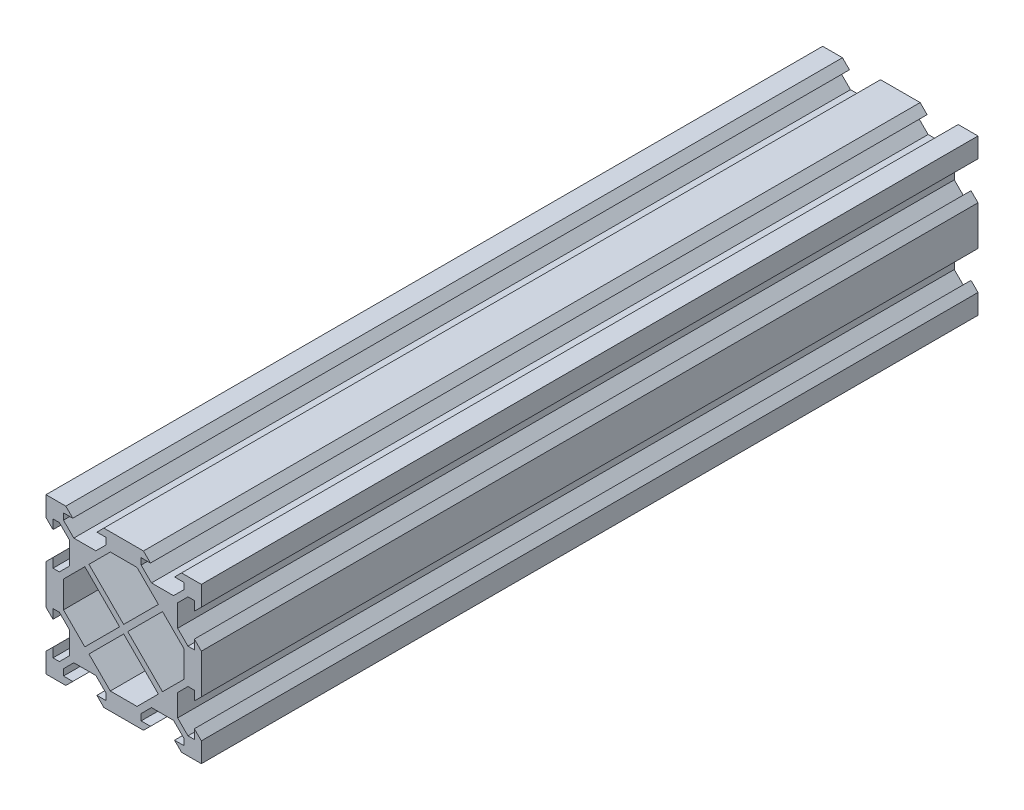
SolidWorks part; units mm, degrees
ref_plane "Front (XY)" through (0, 0, 0) normal (0, 0, 1) x (1, 0, 0)
ref_plane "Top (XZ)" through (0, 0, 0) normal (0, 1, 0) x (1, 0, 0)
ref_plane "Right (YZ)" through (0, 0, 0) normal (1, 0, 0) x (0, 0, -1)
sketch "Sketch2" plane through (0, 0, 0) normal (0, 0, 1) x (1, 0, 0)
  line L0 (-10, 10) -> (10, 10)
  line L1 (10, 10) -> (10, -10)
  line L2 (10, -10) -> (-10, -10)
  line L3 (-10, -10) -> (-10, 10)
  point P4 (0, -10)
  point P6 (10, 0)
  dimension "D1" = 20
  dimension "D2" = 20
extrude "Boss-Extrude1" add sketch "Sketch2" against normal blind 200
sketch "Sketch3" plane through (0, 0, 0) normal (0, 0, 1) x (1, 0, 0)
  line L0 (0, 0) -> (0, 10) construction
  line L1 (0, 10) -> (-3.1, 10) construction
  line L2 (10, 10) -> (-10, 10) construction
  line L3 (-3.1, 10) -> (-3.1, 8.2) construction
  line L4 (3.1, 10) -> (3.1, 8.2) construction
  line L5 (-3.1, 8.2) -> (-4.9, 10)
  line L6 (3.1, 8.2) -> (4.9, 10)
  line L7 (-3.1, 8.2) -> (-5.5, 8.2)
  line L8 (3.1, 8.2) -> (5.5, 8.2)
  line L9 (-5.5, 8.2) -> (-5.5, 6.56)
  line L10 (5.5, 8.2) -> (5.5, 6.56)
  line L11 (0, 10) -> (0, 3.9) construction
  line L12 (2.84, 3.9) -> (-2.84, 3.9)
  line L13 (-2.84, 3.9) -> (-5.5, 6.56)
  line L14 (2.84, 3.9) -> (5.5, 6.56)
  line L15 (-4.9, 10) -> (4.9, 10)
  point P21 (0, 3.9)
  dimension "D1" = 3.1
  dimension "D2" = 1.8
  dimension "D3" = 90
  dimension "D4" = 2.4
  dimension "D5" = 1.64
  dimension "D6" = 6.1
  dimension "D7" = 5.68
extrude "Cut-Extrude1" cut sketch "Sketch3" along normal through all and the other way through all
sketch "Sketch8" plane through (0, 0, 0) normal (1, 0, 0) x (0, 0, -1)
  line L0 (0, 0) -> (-11.2124, 0) construction
  line L1 (0, -10) -> (0, 10) construction
pattern_circular "CirPattern2" count 4 over 360 about axis through (0, 0, 0) along (0, 0, 1) of "Cut-Extrude1"
pattern_linear "LPattern1" count 2 spacing 20 along (0, 1, 0) count 2 spacing 20 along (1, 0, 0) of "Boss-Extrude1", "Cut-Extrude1", "CirPattern2"
sketch "Sketch9" plane through (0, 0, 0) normal (0, 0, 1) x (1, 0, 0)
  line L0 (14.5, 6.56) -> (17.16, 3.9) construction
  line L1 (16.1, 2.84) -> (13.44, 5.5) construction
  line L2 (2.84, 3.9) -> (5.5, 6.56) construction
  line L3 (6.56, 5.5) -> (3.9, 2.84) construction
  line L4 (5.5, 13.44) -> (2.84, 16.1) construction
  line L5 (3.9, 17.16) -> (6.56, 14.5) construction
  line L6 (13.44, 14.5) -> (16.1, 17.16) construction
  line L7 (17.16, 16.1) -> (14.5, 13.44) construction
  line L8 (1.06, 0) -> (6.56, -5.5)
  line L9 (20, 1.06) -> (25.5, 6.56)
  line L10 (16.1, 22.84) -> (13.44, 25.5) construction
  line L11 (25.5, 13.44) -> (22.84, 16.1) construction
  line L12 (25.5, 11.8) -> (25.5, 13.44) construction
  line L13 (25.5, 6.56) -> (25.5, 8.2) construction
  line L14 (22.84, 3.9) -> (25.5, 6.56) construction
  line L16 (6.56, -5.5) -> (13.44, -5.5)
  line L17 (-5.5, 6.56) -> (-2.84, 3.9) construction
  line L18 (-5.5, 8.2) -> (-5.5, 6.56) construction
  line L20 (6.56, 25.5) -> (3.9, 22.84) construction
  line L21 (11.06, 10) -> (20, 1.06)
  line L22 (18.94, 0) -> (10, 8.94)
  line L23 (0, 1.06) -> (8.94, 10)
  line L24 (10, 8.94) -> (1.06, 0)
  line L25 (8.94, 10) -> (0, 18.94)
  line L26 (1.06, 20) -> (10, 11.06)
  line L27 (10, 11.06) -> (18.94, 20)
  line L28 (20, 18.94) -> (11.06, 10)
  line L29 (13.44, 25.5) -> (6.56, 25.5)
  line L31 (18.94, 20) -> (13.44, 25.5)
  line L32 (25.5, 13.44) -> (20, 18.94)
  line L33 (25.5, 11.8) -> (25.5, 13.44)
  line L34 (25.5, 6.56) -> (25.5, 11.8)
  line L35 (13.44, -5.5) -> (18.94, 0)
  line L38 (-5.5, 6.56) -> (0, 1.06)
  line L39 (-5.5, 13.44) -> (-5.5, 6.56)
  line L41 (6.56, 25.5) -> (1.06, 20)
  line L43 (0, 18.94) -> (-5.5, 13.44)
extrude "Cut-Extrude2" cut sketch "Sketch9" against normal through all
